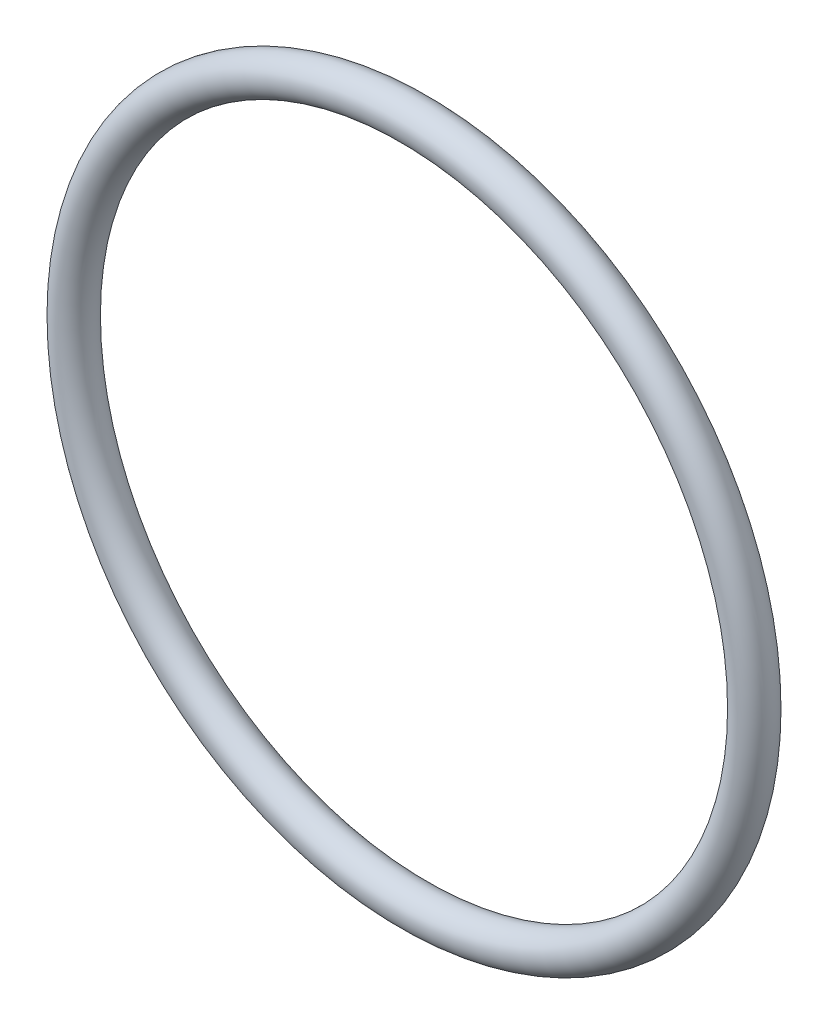
SolidWorks part; units mm, degrees
ref_plane "Front" through (0, 0, 0) normal (0, 0, 1) x (1, 0, 0)
ref_plane "Top" through (0, 0, 0) normal (0, 1, 0) x (1, 0, 0)
ref_plane "Right" through (0, 0, 0) normal (1, 0, 0) x (0, 0, -1)
sketch "Sketch1" plane through (0, 0, 0) normal (1, 0, 0) x (0, -1, 0)
  line L0 (0, -1.5) -> (0, 1.5) construction
  line L2 (-41.8, 0) -> (41.8, 0) construction
  line L3 (-25.5, 0) -> (25.5, 0) construction
  circle A0 centre (27, 0) radius 1.5
  point P9 (25.5, 0)
  point P10 (28.5, 0)
  point P13 (27, 1.5)
  point P14 (27, -1.5)
  dimension "Width" = 3
  dimension "ID" = 51
revolve "Revolve1" add sketch "Sketch1" angle 360 about L0
